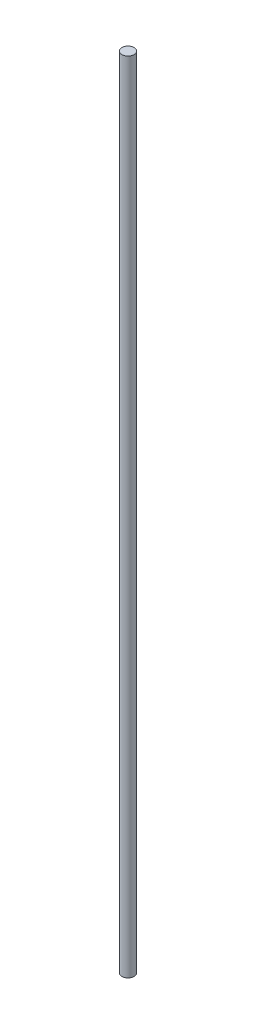
SolidWorks part; units mm, degrees
ref_plane "Front Plane" through (0, 0, 0) normal (0, 0, 1) x (1, 0, 0)
ref_plane "Top Plane" through (0, 0, 0) normal (0, 1, 0) x (1, 0, 0)
ref_plane "Right Plane" through (0, 0, 0) normal (1, 0, 0) x (0, 0, -1)
sketch "Sketch1" plane through (0, 0, 0) normal (0, 1, 0) x (1, 0, 0)
  circle A0 centre (0, 0) radius 1
  dimension "D1" = 2
extrude "Boss-Extrude1" add sketch "Sketch1" along normal blind 130
